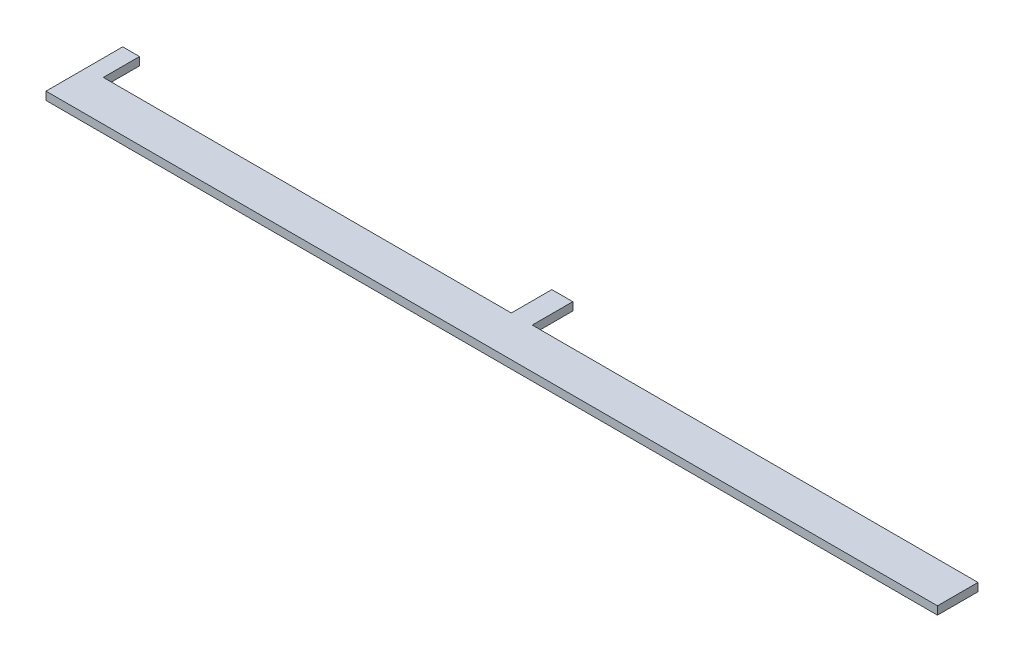
SolidWorks part; units mm, degrees
ref_plane "Front Plane" through (0, 0, 0) normal (0, 0, 1) x (1, 0, 0)
ref_plane "Top Plane" through (0, 0, 0) normal (0, 1, 0) x (1, 0, 0)
ref_plane "Right Plane" through (0, 0, 0) normal (1, 0, 0) x (0, 0, -1)
sketch "Sketch1" plane through (0, 0, 0) normal (0, 1, 0) x (1, 0, 0)
  line L0 (0, 0) -> (0, 15) construction
  line L1 (110, -5) -> (-110, -5)
  line L2 (110, -5) -> (110, 5)
  line L3 (110, 5) -> (0, 5)
  line L4 (-110, -5) -> (-110, 5)
  line L5 (110, -5) -> (0, 0) construction
  line L6 (110, 5) -> (-110, -5) construction
  line L7 (-5.1649, 5) -> (-5.1649, 15)
  line L8 (-5.1649, 15) -> (0, 15)
  line L9 (0, 15) -> (0, 5)
  line L10 (-5.1649, 5) -> (-105.8536, 5)
  line L11 (-110, 5) -> (-110, 13.9309)
  line L12 (-110, 13.9309) -> (-105.8536, 13.9309)
  line L13 (-105.8536, 13.9309) -> (-105.8536, 5)
  point P0 (0, 0)
  dimension "D1" = 220
  dimension "D2" = 10
  dimension "D3" = 10
extrude "Boss-Extrude1" add sketch "Sketch1" along normal blind 2
